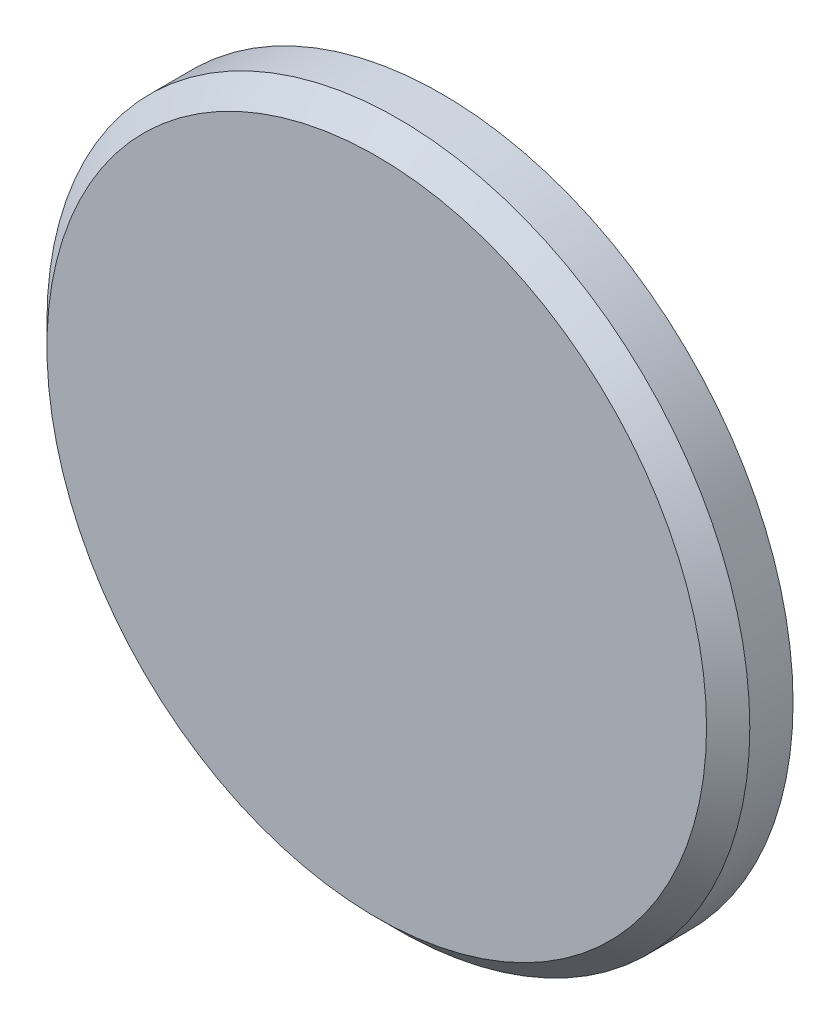
SolidWorks part; units mm, degrees
ref_plane "Plane1" through (0, 0, 0) normal (0, 0, 1) x (1, 0, 0)
ref_plane "Plane2" through (0, 0, 0) normal (0, 1, 0) x (1, 0, 0)
ref_plane "Plane3" through (0, 0, 0) normal (1, 0, 0) x (0, 0, -1)
sketch "Esquisse1" plane through (0, 0, 0) normal (0, 0, 1) x (1, 0, 0)
  circle A0 centre (0, 0) radius 16.25
  dimension "D1" = 32.5
extrude "couvercle" add sketch "Esquisse1" along normal blind 3
chamfer "Chanfrein" distance 1 angle 45
